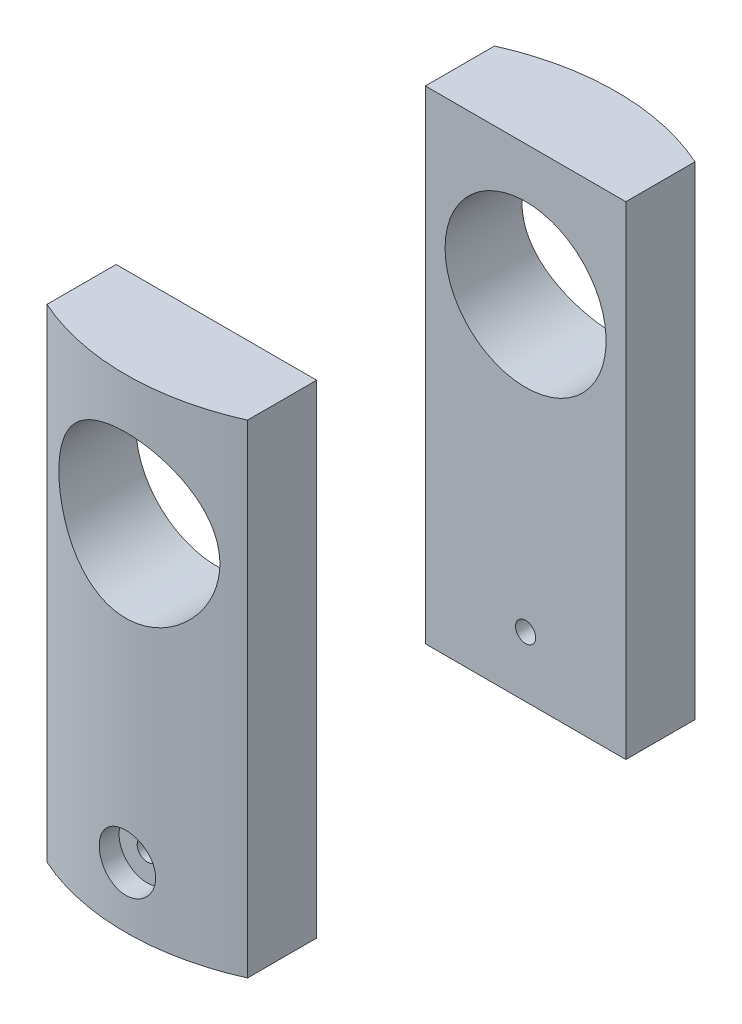
SolidWorks part; units mm, degrees
ref_plane "Front Plane" through (0, 0, 0) normal (0, 0, 1) x (1, 0, 0)
ref_plane "Top Plane" through (0, 0, 0) normal (0, 1, 0) x (1, 0, 0)
ref_plane "Right Plane" through (0, 0, 0) normal (1, 0, 0) x (0, 0, -1)
sketch "Sketch3" plane through (0, 0, 0) normal (0, 1, 0) x (1, 0, 0)
  line L0 (-31.623, 48.768) -> (31.623, 48.768)
  line L1 (-31.623, 48.768) -> (-31.623, 70.5828)
  line L2 (31.623, 48.768) -> (31.623, 70.5828)
  line L3 (0, 0) -> (65.567, 0) construction
  line L4 (-31.623, -48.768) -> (31.623, -48.768)
  line L5 (-31.623, -48.768) -> (-31.623, -70.5828)
  line L6 (31.623, -48.768) -> (31.623, -70.5828)
  arc A0 (31.623, 70.5828) -> (-31.623, 70.5828) centre (0, 0) ccw
  arc A1 (31.623, -70.5828) -> (-31.623, -70.5828) centre (0, 0) cw
  point P4 (0, 0)
  point P9 (0, 48.768)
  dimension "D1" = 63.246
  dimension "D2" = 48.768
extrude "Boss-Extrude1" add sketch "Sketch3" along normal blind 152.4
sketch "Sketch4" plane through (0, 0, -48.768) normal (0, 0, 1) x (1, 0, 0)
  line L0 (0, 0) -> (0, 99.7288) construction
  line L1 (-31.623, 0) -> (31.623, 0) construction
  circle A0 centre (0, 19.05) radius 3.175
  point P6 (0, 0)
  dimension "D1" = 19.05
extrude "Cut-Extrude1" cut sketch "Sketch4" against normal blind 30.48 and the other way blind 127
sketch "Sketch5" plane through (0, 0, -48.768) normal (0, 0, 1) x (1, 0, 0)
  line L0 (0, 0) -> (0, 152.4) construction
  line L1 (-31.623, 0) -> (31.623, 0) construction
  line L2 (-31.623, 152.4) -> (31.623, 152.4) construction
  circle A0 centre (0, 111.241) radius 25.4
extrude "Cut-Extrude2" cut sketch "Sketch5" against normal blind 30.48 and the other way blind 127
ref_plane "Plane1" through (0, 0, -70.5828) normal (0, 0, -1) x (-1, 0, 0)
sketch "Sketch6" plane through (0, 0, -70.5828) normal (0, 0, -1) x (-1, 0, 0)
  circle A0 centre (0, 19.05) radius 8.89
extrude "Cut-Extrude3" cut sketch "Sketch6" along normal blind 10.16
ref_plane "Plane2" through (0, 0, 70.5828) normal (0, 0, 1) x (1, 0, 0)
sketch "Sketch7" plane through (0, 0, 70.5828) normal (0, 0, 1) x (1, 0, 0)
  circle A0 centre (0, 19.05) radius 8.89
extrude "Cut-Extrude4" cut sketch "Sketch7" along normal blind 10.16
